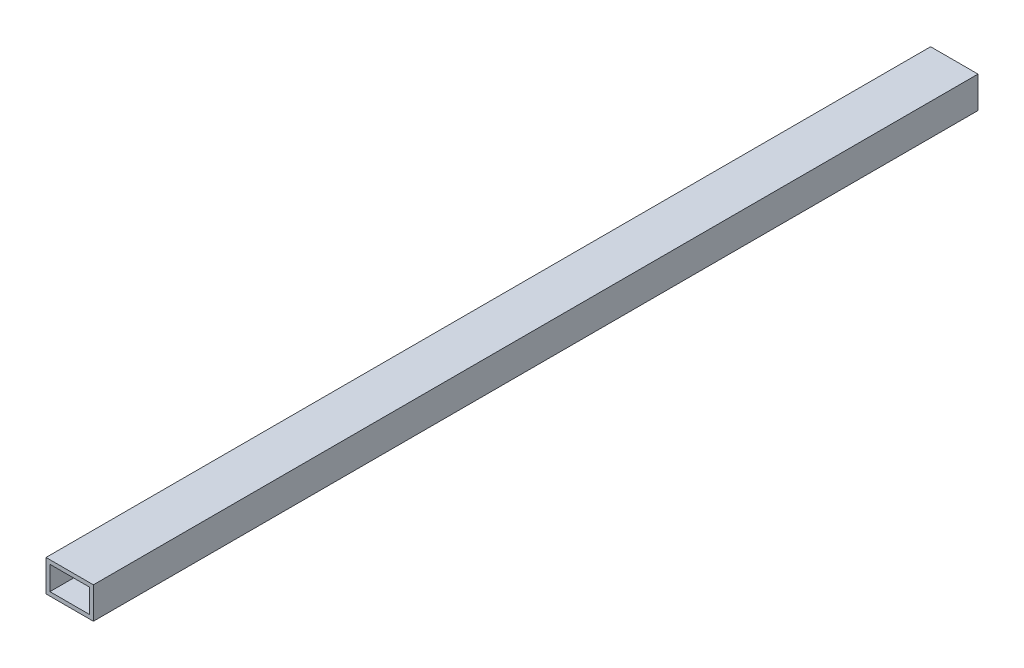
SolidWorks part; units mm, degrees
material "6061 Alloy"
ref_plane "Front Plane" through (0, 0, 0) normal (0, 0, 1) x (1, 0, 0)
ref_plane "Top Plane" through (0, 0, 0) normal (0, 1, 0) x (1, 0, 0)
ref_plane "Right Plane" through (0, 0, 0) normal (1, 0, 0) x (0, 0, -1)
sketch "Sketch1" plane through (0, 0, 0) normal (0, 0, 1) x (1, 0, 0)
  line L0 (19.05, 0) -> (15.875, 0) construction
  line L1 (-19.05, 0) -> (19.05, 0) construction
  line L2 (0, 12.7) -> (0, -12.7)
  point P7 (0, 0)
sketch "Sketch2" plane through (0, 0, 0) normal (1, 0, 0) x (0, 0, -1)
  line L0 (355.6, 0) -> (-355.6, 0)
  point P4 (0, 0)
  dimension "Length" = 711.2
sketch "Sketch3" plane through (0, 0, 0) normal (0, 0, 1) x (1, 0, 0)
  line L0 (-19.05, 0) -> (19.05, 0) construction
  line L5 (19.05, -12.7) -> (-19.05, -12.7)
  line L6 (19.05, -12.7) -> (19.05, 12.7)
  line L11 (19.05, 12.7) -> (-19.05, 12.7)
  line L12 (-19.05, -12.7) -> (-19.05, 12.7)
  line L14 (19.05, -12.7) -> (-19.05, 12.7) construction
  line L15 (19.05, 12.7) -> (-19.05, -12.7) construction
  line L16 (15.875, -9.525) -> (-15.875, -9.525)
  line L17 (15.875, -9.525) -> (15.875, 9.525)
  line L18 (15.875, 9.525) -> (-15.875, 9.525)
  line L19 (-15.875, -9.525) -> (-15.875, 9.525)
  line L20 (15.875, -9.525) -> (-15.875, 9.525) construction
  line L21 (15.875, 9.525) -> (-15.875, -9.525) construction
  point P0 (0, 0)
  point P5 (0, 0)
  point P13 (15.875, -12.7)
  dimension "D1" = 3.175
  dimension "D3" = 38.1
  dimension "D4" = 25.4
  dimension "D2" = 3.175
extrude "Boss-Extrude1" add sketch "Sketch3" along normal up to vertex (355.6 mm away) and the other way up to vertex (355.6 mm away) up to point (0, 0, 355.6) other way up to point (0, 0, -355.6)
sketch "Sketch5" plane through (0, 0, 0) normal (1, 0, 0) x (0, 0, -1)
  line L0 (-355.6, 0) -> (355.6, 0) construction
  line L3 (-355.6, -12.7) -> (-355.6, 12.7) construction
  line L4 (355.6, -12.7) -> (355.6, 12.7) construction
  point P6 (-312.7375, 0)
  point P7 (-298.45, 0)
  point P8 (298.45, 0)
  point P10 (312.7375, 0)
  dimension "D1" = 42.8625
  dimension "D2" = 57.15
  dimension "D3" = 42.8625
  dimension "D4" = 57.15
equation "\"D1@Sketch3\"=\"Wall thickness@Sketch1\""
equation "\"D1@Sketch5\"=\"Width@Sketch1\"*1.125"
equation "\"D2@Sketch5\"=\"Width@Sketch1\"*1.5"
equation "\"D3@Sketch5\"=\"D1@Sketch5\""
equation "\"D4@Sketch5\"=\"D2@Sketch5\""
equation "\"D2@Sketch3\"=\"Wall Thickness@Sketch1\""
